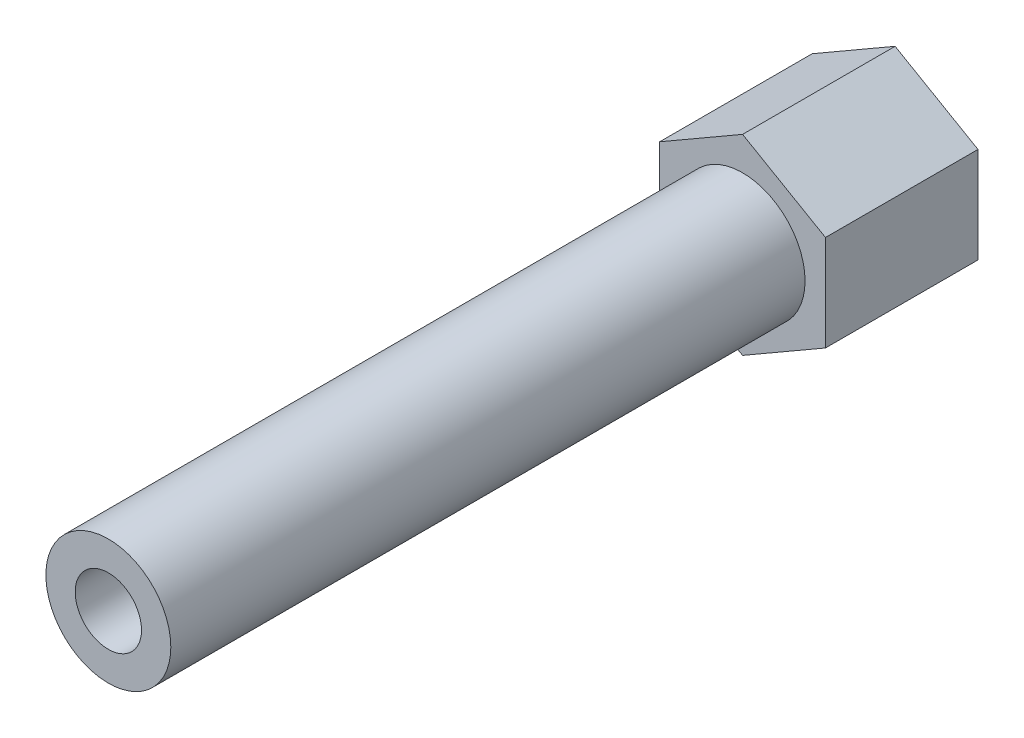
SolidWorks part; units mm, degrees
ref_plane "Alzado" through (0, 0, 0) normal (0, 0, 1) x (1, 0, 0)
ref_plane "Planta" through (0, 0, 0) normal (0, 1, 0) x (1, 0, 0)
ref_plane "Vista lateral" through (0, 0, 0) normal (1, 0, 0) x (0, 0, -1)
sketch "Croquis1" plane through (0, 0, 0) normal (0, 0, 1) x (1, 0, 0)
  line L0 (0, 0) -> (0, 7.2169) construction
  line L2 (0, 7.2169) -> (-6.25, 3.6084)
  line L3 (-6.25, 3.6084) -> (-6.25, -3.6084)
  line L4 (-6.25, -3.6084) -> (0, -7.2169)
  line L5 (0, -7.2169) -> (6.25, -3.6084)
  line L6 (6.25, -3.6084) -> (6.25, 3.6084)
  line L7 (6.25, 3.6084) -> (0, 7.2169)
  circle A0 centre (0, 0) radius 6.25 construction
  dimension "D1" = 12.5
extrude "Saliente-Extruir1" add sketch "Croquis1" along normal blind 11.5
sketch "Croquis2" plane through (0, 0, 11.5) normal (0, 0, 1) x (1, 0, 0)
  circle A0 centre (0, 0) radius 4.71
  dimension "D1" = 9.42
extrude "Saliente-Extruir2" add sketch "Croquis2" along normal blind 47.82
sketch "Croquis3" plane through (0, 0, 59.32) normal (0, 0, 1) x (1, 0, 0)
  circle A0 centre (0, 0) radius 2.5
  dimension "D1" = 5
extrude "Cortar-Extruir1" cut sketch "Croquis3" against normal blind 10
